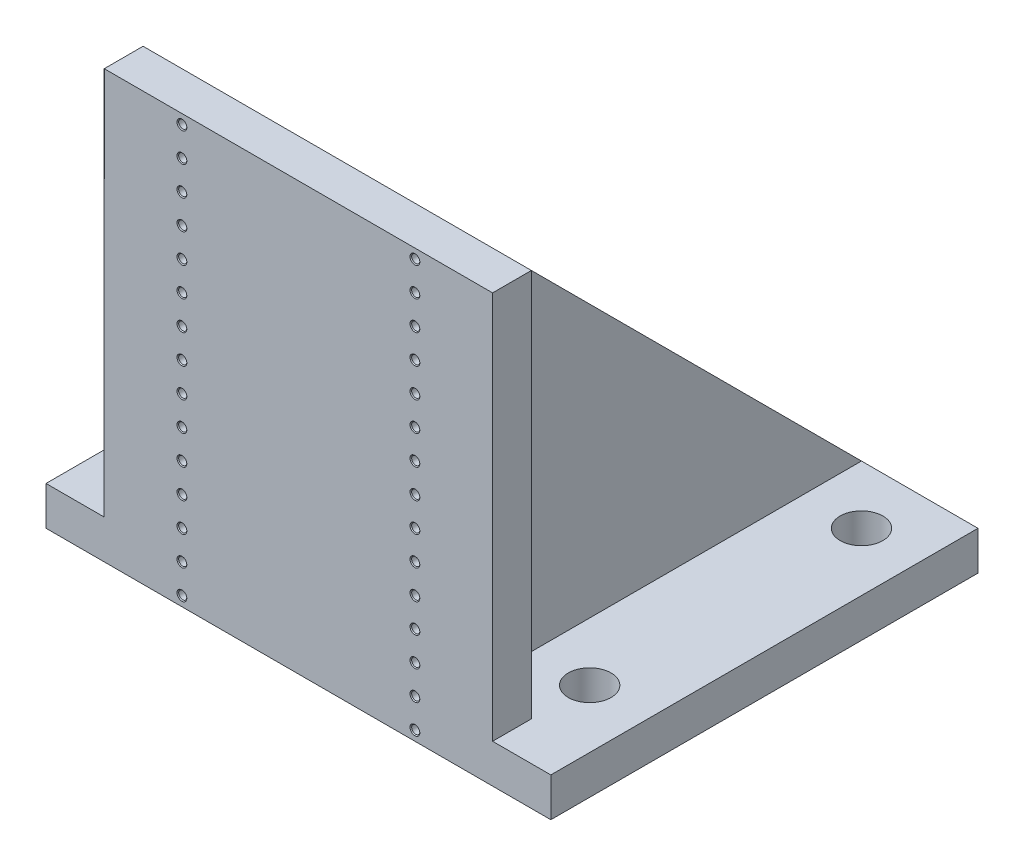
SolidWorks part; units mm, degrees
other "Item de detalhe2"
other "Item de detalhe3"
other "Item de detalhe4"
other "Item de detalhe5"
other "Item de detalhe6"
other "Pasta de soldas"
other "Cordão de solda...2"
other "Cordão de solda...3"
other "Cordão de solda...4"
other "Cordão de solda...5"
other "Cordão de solda...6"
material "AISI 1020"
ref_plane "Plano frontal" through (0, 0, 0) normal (0, 0, 1) x (1, 0, 0)
ref_plane "Plano superior" through (0, 0, 0) normal (0, 1, 0) x (1, 0, 0)
ref_plane "Plano direito" through (0, 0, 0) normal (1, 0, 0) x (0, 0, -1)
sketch "Esboço1" plane through (0, 0, 0) normal (0, 0, 1) x (1, 0, 0)
  line L1 (-100, 200) -> (100, 200)
  line L2 (-100, 200) -> (-100, 0)
  line L3 (-100, 0) -> (100, 0)
  line L4 (100, 200) -> (100, 0)
  line L5 (-100, 200) -> (100, 0) construction
  line L6 (-100, 0) -> (100, 200) construction
  point P0 (0, 100)
  point P5 (0, 0)
  dimension "D1" = 200
  dimension "D2" = 200
extrude "Ressalto-extrusão1" add sketch "Esboço1" against normal blind 20
ref_plane "Plano1" through (60, 0, 0) normal (1, 0, 0) x (0, 0, -1)
sketch "Esboço2" plane through (60, 0, 0) normal (1, 0, 0) x (0, 0, -1)
  line L0 (20, 0) -> (20, 200) construction
  line L1 (20, 0) -> (20, 200)
  line L2 (20, 0) -> (220, 0)
  line L3 (220, 0) -> (20, 200)
  dimension "D1" = 45
extrude "Ressalto-extrusão2" add sketch "Esboço2" along normal blind 10 and the other way blind 10
mirror "Espelhar1" about plane through (0, 0, 0) normal (1, 0, 0) of "Ressalto-extrusão2"
sketch "Esboço3" plane through (0, 0, 0) normal (0, -1, 0) x (1, 0, 0)
  line L0 (-100, 0) -> (100, 0) construction
  line L1 (-130, -220) -> (130, -220)
  line L2 (-130, -220) -> (-130, 0)
  line L3 (-130, 0) -> (130, 0)
  line L4 (130, -220) -> (130, 0)
  line L5 (-130, -220) -> (130, 0) construction
  line L6 (-130, 0) -> (130, -220) construction
  line L7 (0, 0) -> (0, -220) construction
  line L8 (70, -20) -> (70, -220) construction
  line L10 (-50, -220) -> (-70, -220) construction
  point P0 (0, -110)
  dimension "D1" = 60
extrude "Ressalto-extrusão3" add sketch "Esboço3" along normal blind 20
sketch "Esboço4" plane through (0, 0, 0) normal (0, 1, 0) x (1, 0, 0)
  line L0 (-130, 190) -> (-70, 190) construction
  line L1 (-130, 0) -> (-130, 220) construction
  line L2 (-70, 220) -> (-70, 20) construction
  line L3 (-50, 190) -> (50, 190) construction
  line L4 (-50, 20) -> (-50, 220) construction
  line L5 (50, 220) -> (50, 20) construction
  line L6 (70, 190) -> (130, 190) construction
  line L7 (70, 220) -> (70, 20) construction
  line L8 (130, 220) -> (130, 0) construction
  line L9 (-130, 220) -> (-70, 220) construction
  line L14 (100, 190) -> (100, 220) construction
  line L15 (70, 220) -> (130, 220) construction
  line L17 (-100, 190) -> (-100, 220) construction
  circle A1 centre (0, 190) radius 11
  dimension "D2" = 22
  dimension "D1" = 30
extrude "Corte-extrusão1" cut sketch "Esboço4" against normal up to next
pattern_linear "Padrão linear1" count 2 spacing 100 along (1, 0, 0) count 2 spacing 100 along (-1, 0, 0) of "Corte-extrusão1"
pattern_linear "Padrão linear2" count 2 spacing 140 along (0, 0, 1) of "Padrão linear1", "Corte-extrusão1"
sketch "Esboço6" plane through (0, 0, 0) normal (0, 0, 1) x (1, 0, 0)
  line L0 (0, 200) -> (0, -20) construction
  line L1 (100, 200) -> (-100, 200) construction
  line L2 (130, -20) -> (-130, -20) construction
  line L3 (-60, 200) -> (-60, -20) construction
  line L4 (-50, 200) -> (-70, 200) construction
  circle A0 centre (-60, -15) radius 2.5
  dimension "D2" = 5
  dimension "D1" = 60
  dimension "D3" = 5
hole_wizard "Furo roscado de M51" positions "3DSketch1" profile "Esboço7" tap size "M5" standard "ISO"
sketch3d "3DSketch1"
  point P0 (-60, -15, 0)
cosmetic thread "Rosca de furo1" parameters "D1"=30, "D2"=5
sketch "Esboço7" plane through (-60, -15, 0) normal (1, 0, 0) x (0, -1, 0)
  line L0 (0, 0) -> (0, 28.2618)
  line L1 (0, 28.2618) -> (2.1, 27)
  line L2 (2.1, 27) -> (2.1, 0.425)
  line L3 (2.1, 0.425) -> (2.525, 0)
  line L5 (2.525, 0) -> (0, 0)
  line L6 (-2.1, 0.425) -> (-2.525, 0) construction
  line L10 (0, 28.2618) -> (-2.1, 27) construction
  line L11 (0, -6.35) -> (0, 107.95) construction
  dimension "Tap Drill Dia." = 4.2
  dimension "Tap Drill Depth" = 27
  dimension "Near C'Sink Dia." = 5.05
  dimension "Near C'Sink Angle" = 90
  dimension "Drill Angle" = 118
pattern_linear "Padrão linear3" count 15 spacing 15 along (0, 1, 0) of "Furo roscado de M51"
cosmetic thread "Rosca de furo2" parameters "D1"=30, "D2"=5
cosmetic thread "Rosca de furo3" parameters "D1"=30, "D2"=5
cosmetic thread "Rosca de furo4" parameters "D1"=30, "D2"=5
cosmetic thread "Rosca de furo5" parameters "D1"=30, "D2"=5
cosmetic thread "Rosca de furo6" parameters "D1"=30, "D2"=5
cosmetic thread "Rosca de furo7" parameters "D1"=30, "D2"=5
cosmetic thread "Rosca de furo8" parameters "D1"=30, "D2"=5
cosmetic thread "Rosca de furo9" parameters "D1"=30, "D2"=5
cosmetic thread "Rosca de furo10" parameters "D1"=30, "D2"=5
cosmetic thread "Rosca de furo11" parameters "D1"=30, "D2"=5
cosmetic thread "Rosca de furo12" parameters "D1"=30, "D2"=5
cosmetic thread "Rosca de furo13" parameters "D1"=30, "D2"=5
cosmetic thread "Rosca de furo14" parameters "D1"=30, "D2"=5
cosmetic thread "Rosca de furo15" parameters "D1"=30, "D2"=5
cosmetic thread "Rosca de furo16" parameters "D1"=30, "D2"=5
cosmetic thread "Rosca de furo17" parameters "D1"=30, "D2"=5
cosmetic thread "Rosca de furo18" parameters "D1"=30, "D2"=5
cosmetic thread "Rosca de furo19" parameters "D1"=30, "D2"=5
cosmetic thread "Rosca de furo20" parameters "D1"=30, "D2"=5
cosmetic thread "Rosca de furo21" parameters "D1"=30, "D2"=5
mirror "Espelhar2" about plane through (0, 0, 0) normal (1, 0, 0) of "Padrão linear3", "Furo roscado de M51"
cosmetic thread "Rosca de furo22" parameters "D1"=30, "D2"=5
cosmetic thread "Rosca de furo23" parameters "D1"=30, "D2"=5
cosmetic thread "Rosca de furo24" parameters "D1"=30, "D2"=5
cosmetic thread "Rosca de furo25" parameters "D1"=30, "D2"=5
cosmetic thread "Rosca de furo26" parameters "D1"=30, "D2"=5
cosmetic thread "Rosca de furo27" parameters "D1"=30, "D2"=5
cosmetic thread "Rosca de furo28" parameters "D1"=30, "D2"=5
cosmetic thread "Rosca de furo29" parameters "D1"=30, "D2"=5
cosmetic thread "Rosca de furo30" parameters "D1"=30, "D2"=5
cosmetic thread "Rosca de furo31" parameters "D1"=30, "D2"=5
cosmetic thread "Rosca de furo32" parameters "D1"=30, "D2"=5
cosmetic thread "Rosca de furo33" parameters "D1"=30, "D2"=5
cosmetic thread "Rosca de furo34" parameters "D1"=30, "D2"=5
cosmetic thread "Rosca de furo35" parameters "D1"=30, "D2"=5
cosmetic thread "Rosca de furo36" parameters "D1"=30, "D2"=5
cosmetic thread "Rosca de furo37" parameters "D1"=30, "D2"=5
cosmetic thread "Rosca de furo38" parameters "D1"=30, "D2"=5
cosmetic thread "Rosca de furo39" parameters "D1"=30, "D2"=5
cosmetic thread "Rosca de furo40" parameters "D1"=30, "D2"=5
cosmetic thread "Rosca de furo41" parameters "D1"=30, "D2"=5
cosmetic thread "Rosca de furo42" parameters "D1"=30, "D2"=5
